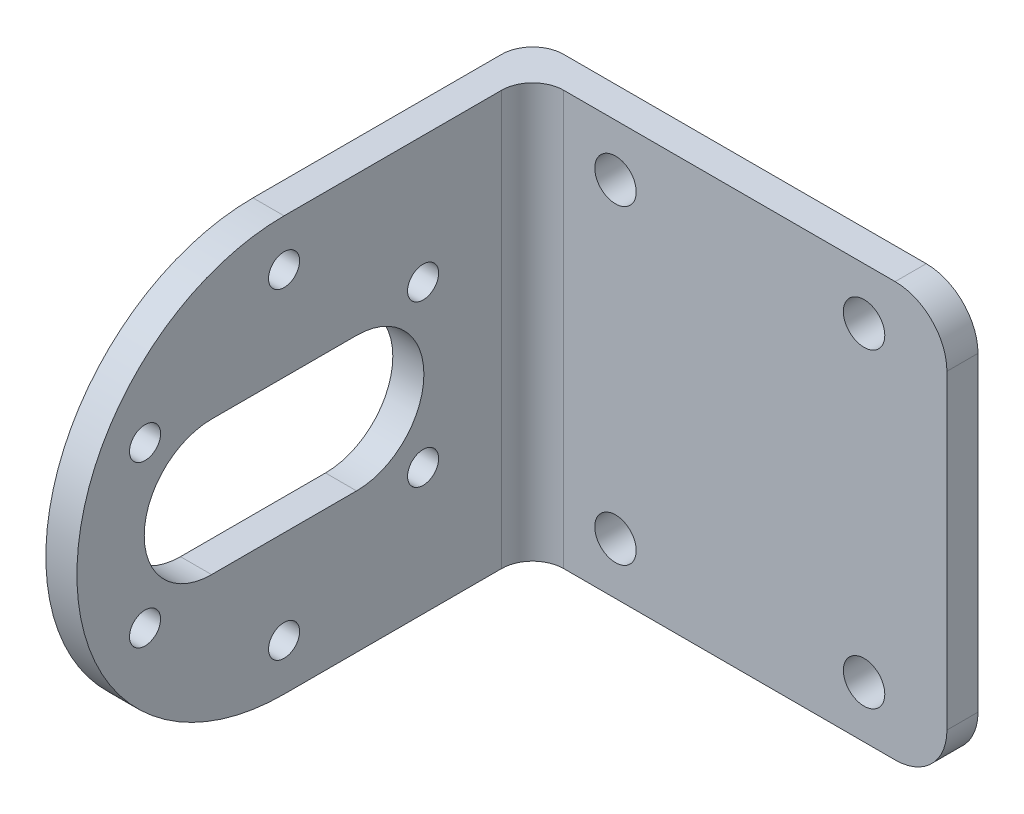
SolidWorks part; units mm, degrees
ref_plane "前视基准面" through (0, 0, 0) normal (0, 0, 1) x (1, 0, 0)
ref_plane "上视基准面" through (0, 0, 0) normal (0, 1, 0) x (1, 0, 0)
ref_plane "右视基准面" through (0, 0, 0) normal (1, 0, 0) x (0, 0, -1)
other "Configuration Table"
sketch "草图1" plane through (0, 0, 0) normal (0, 0, 1) x (1, 0, 0)
  line L1 (0, 0) -> (40, 0)
  line L2 (0, 0) -> (0, 40)
  line L3 (0, 40) -> (40, 40)
  line L4 (40, 0) -> (40, 40)
  circle A0 centre (8, 35) radius 2
  circle A1 centre (32, 35) radius 2
  circle A2 centre (32, 5) radius 2
  circle A3 centre (8, 5) radius 2
  point P4 (8, 35)
  point P5 (32, 35)
  point P7 (32, 5)
  point P8 (8, 5)
  dimension "D1" = 40
  dimension "D2" = 40
  dimension "D3" = 24
  dimension "D4" = 8
  dimension "D5" = 30
  dimension "D6" = 5
extrude "凸台-拉伸1" add sketch "草图1" along normal blind 3
fillet "圆角1" radius 5 2 edges at (40, 0, 1.5) (40, 40, 1.5)
sketch "草图2" plane through (0, 0, 0) normal (-1, 0, 0) x (0, 0, 1)
  line L0 (0, 40) -> (27, 40)
  line L1 (0, 0) -> (27, 0)
  line L2 (0, 40) -> (0, 0)
  line L10 (20, 26.5) -> (34, 26.5)
  line L12 (20, 13.5) -> (34, 13.5)
  arc A0 (27, 0) -> (27, 40) centre (27, 20) ccw
  circle A1 centre (27, 20) radius 15.5 construction
  circle A2 centre (27, 35.5) radius 1.5
  circle A3 centre (40.4234, 27.75) radius 1.5
  circle A4 centre (40.4234, 12.25) radius 1.5
  circle A5 centre (27, 4.5) radius 1.5
  circle A6 centre (13.5766, 12.25) radius 1.5
  circle A7 centre (13.5766, 27.75) radius 1.5
  arc A8 (20, 26.5) -> (20, 13.5) centre (20, 20) ccw
  arc A10 (34, 13.5) -> (34, 26.5) centre (34, 20) ccw
  point P7 (27, 35.5)
  point P24 (27, 20)
  point P26 (40.5, 20)
  point P28 (13.5, 20)
  dimension "D1" = 6
extrude "凸台-拉伸2" add sketch "草图2" along normal blind 3 contours A4 | A5 | A7 | A3 | A2 | L12 A10 L10 A8 | A0 L0 L2 L1 | A6
fillet "圆角2" radius 3 2 edges at (-3, 20, 0) (0, 20, 3)
